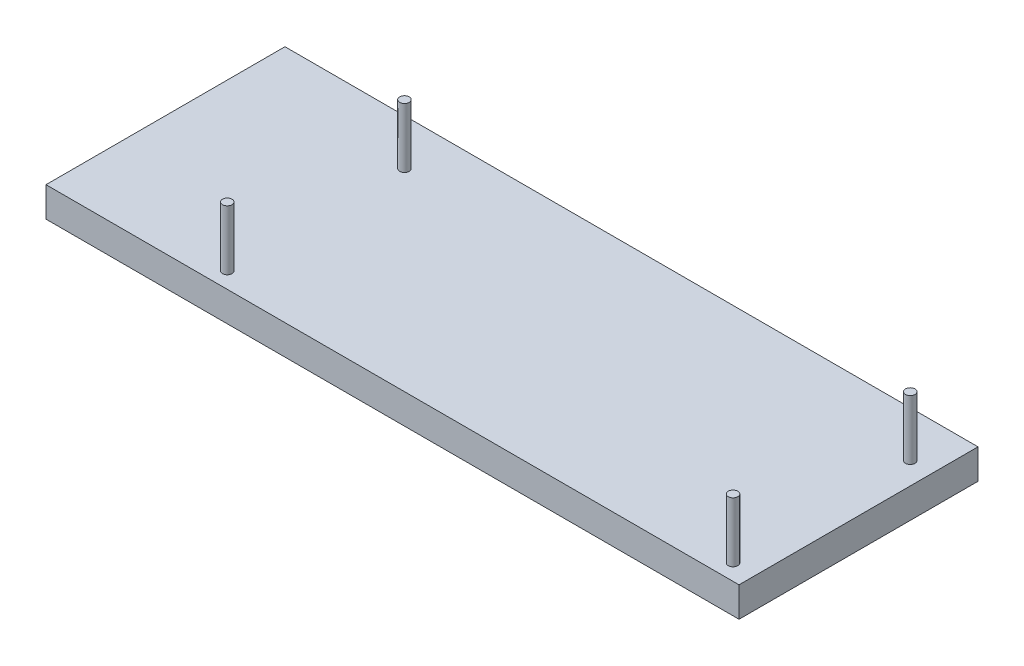
SolidWorks part; units mm, degrees
ref_plane "Front Plane" through (0, 0, 0) normal (0, 0, 1) x (1, 0, 0)
ref_plane "Top Plane" through (0, 0, 0) normal (0, 1, 0) x (1, 0, 0)
ref_plane "Right Plane" through (0, 0, 0) normal (1, 0, 0) x (0, 0, -1)
sketch "Sketch2" plane through (0, 0, 0) normal (0, 1, 0) x (1, 0, 0)
  line L1 (-58, 40) -> (58, 40)
  line L2 (-58, 40) -> (-58, 0)
  line L3 (-58, 0) -> (58, 0)
  line L4 (58, 40) -> (58, 0)
  point P6 (0, 0)
  dimension "D1" = 40
  dimension "D2" = 116
extrude "Boss-Extrude1" add sketch "Sketch2" along normal blind 5
sketch "Sketch3" plane through (0, 5, 0) normal (0, 1, 0) x (1, 0, 0)
  line L0 (58, 40) -> (-58, 40) construction
  line L1 (-58, 0) -> (58, 0) construction
  line L2 (58, 0) -> (58, 40) construction
  line L4 (-58, 40) -> (-58, 0) construction
  circle A0 centre (54.33, 32.33) radius 0.8
  circle A1 centre (54.33, 2.67) radius 0.8
  circle A2 centre (-30.33, 2.67) radius 0.8
  circle A3 centre (-30.33, 32.33) radius 0.8
  dimension "D1" = 1.6
  dimension "D2" = 7.67
  dimension "D3" = 3.67
  dimension "D4" = 3.67
  dimension "D5" = 2.67
  dimension "D6" = 7.67
  dimension "D7" = 27.67
  dimension "D8" = 27.67
  dimension "D9" = 2.67
extrude "Boss-Extrude4" add sketch "Sketch3" along normal blind 10 contours A1 | A0 | A2 | A3
